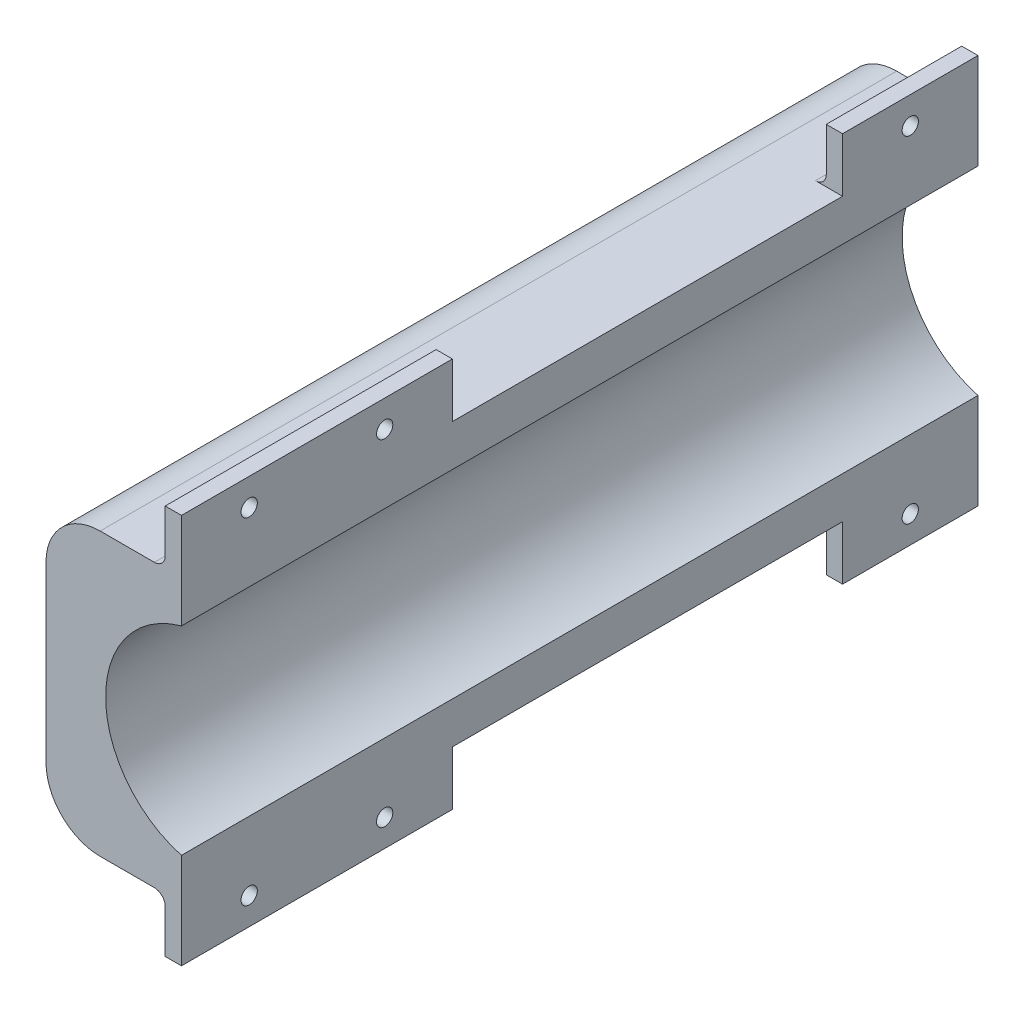
SolidWorks part; units mm, degrees
ref_plane "Front Plane" through (0, 0, 0) normal (0, 0, 1) x (1, 0, 0)
ref_plane "Top Plane" through (0, 0, 0) normal (0, 1, 0) x (1, 0, 0)
ref_plane "Right Plane" through (0, 0, 0) normal (1, 0, 0) x (0, 0, -1)
sketch "Sketch1" plane through (0, 0, 0) normal (0, 0, 1) x (1, 0, 0)
  line L0 (-91.4595, 15.9587) -> (-116.4595, 15.9587)
  line L1 (-91.4595, -36.0413) -> (-116.4595, -36.0413)
  line L2 (-116.4595, -36.0413) -> (-116.4595, 15.9587)
  line L3 (-91.4595, -28.3716) -> (-91.4595, -36.0413)
  line L4 (-91.4595, 15.9587) -> (-91.4595, 8.289)
  arc A0 (-91.4595, 8.289) -> (-91.4595, -28.3716) centre (-86.4595, -10.0413) ccw construction
  arc A1 (-91.4595, 8.289) -> (-91.4595, -28.3716) centre (-86.4595, -10.0413) ccw
extrude "Boss-Extrude1" add sketch "Sketch1" against normal blind 147
sketch "Sketch2" plane through (-91.4595, 0, 0) normal (1, 0, 0) x (0, 0, -1)
  line L0 (0, 15.9587) -> (50, 15.9587)
  line L1 (147, 15.9587) -> (0, 15.9587) construction
  line L2 (50, 5.9587) -> (50, 15.9587) construction
  line L3 (147, 15.9587) -> (122, 15.9587)
  line L4 (122, 15.9587) -> (122, 10.9587) construction
  line L5 (0, -10.0413) -> (147, -10.0413) construction
  line L6 (0, 8.289) -> (0, -28.3716) construction
  line L7 (147, -28.3716) -> (147, 8.289) construction
  line L8 (0, 15.9587) -> (12.5, 15.9587) construction
  line L9 (12.5, 15.9587) -> (12.5, 20.9587) construction
  line L10 (25, 15.9587) -> (25, 33.8054) construction
  line L11 (0, 15.9587) -> (0, 25.9587)
  line L12 (0, 25.9587) -> (50, 25.9587)
  line L13 (50, 25.9587) -> (50, 15.9587)
  line L14 (25, -36.0413) -> (25, -53.888) construction
  line L15 (12.5, -36.0413) -> (12.5, -41.0413) construction
  line L16 (0, -36.0413) -> (12.5, -36.0413) construction
  line L17 (50, -46.0413) -> (50, -36.0413)
  line L18 (0, -46.0413) -> (50, -46.0413)
  line L19 (0, -36.0413) -> (0, -46.0413)
  line L20 (0, -36.0413) -> (50, -36.0413)
  line L21 (134.5, 15.9587) -> (134.5, 20.9587) construction
  line L22 (122, 15.9587) -> (122, 25.9587)
  line L23 (122, 25.9587) -> (147, 25.9587)
  line L24 (147, 25.9587) -> (147, 15.9587)
  line L25 (134.5, -36.0413) -> (134.5, -41.0413) construction
  line L26 (147, -46.0413) -> (147, -36.0413)
  line L27 (122, -46.0413) -> (147, -46.0413)
  line L28 (122, -36.0413) -> (122, -46.0413)
  line L29 (147, -36.0413) -> (122, -36.0413)
  circle A0 centre (12.5, 20.9587) radius 1.5
  circle A1 centre (37.5, 20.9587) radius 1.5
  circle A2 centre (37.5, -41.0413) radius 1.5
  circle A3 centre (12.5, -41.0413) radius 1.5
  circle A4 centre (134.5, 20.9587) radius 1.5
  circle A5 centre (134.5, -41.0413) radius 1.5
extrude "Boss-Extrude2" add sketch "Sketch2" against normal blind 3
fillet "Fillet1" radius 10 2 edges at (-116.4595, 15.9587, -73.5) (-116.4595, -36.0413, -73.5)
fillet "Fillet2" radius 2 4 edges at (-94.4595, -36.0413, -25) (-94.4595, -36.0413, -134.5) (-94.4595, 15.9587, -134.5) (-94.4595, 15.9587, -25)
sketch "Sketch3" plane through (0, 0, 0) normal (0, 0, 1) x (1, 0, 0)
  line L5 (-91.4595, 15.9587) -> (-116.4595, 15.9587)
  line L6 (-116.4595, 15.9587) -> (-116.4595, -36.0413)
  line L7 (-116.4595, -36.0413) -> (-91.4595, -36.0413)
  line L8 (-91.4595, -36.0413) -> (-91.4595, -28.3716)
  line L9 (-91.4595, 8.289) -> (-91.4595, 15.9587)
  line L10 (-91.4595, 15.9587) -> (-116.4595, 15.9587)
  line L11 (-116.4595, 15.9587) -> (-116.4595, -36.0413)
  line L12 (-116.4595, -36.0413) -> (-91.4595, -36.0413)
  line L13 (-91.4595, -36.0413) -> (-91.4595, -28.3716)
  line L14 (-91.4595, 8.289) -> (-91.4595, 15.9587)
  arc A1 (-91.4595, 8.289) -> (-91.4595, -28.3716) centre (-86.4595, -10.0413) ccw
  arc A2 (-91.4595, 8.289) -> (-91.4595, -28.3716) centre (-86.4595, -10.0413) ccw
  dimension "D1" = 0
sketch "Sketch4" plane through (-91.4595, 0, 0) normal (1, 0, 0) x (0, 0, -1)
  line L4 (50, 25.9587) -> (0, 25.9587)
  line L5 (50, 15.9587) -> (50, 25.9587)
  line L6 (0, 15.9587) -> (50, 15.9587)
  line L7 (0, 25.9587) -> (0, 15.9587)
  line L8 (50, 25.9587) -> (0, 25.9587)
  line L9 (50, 15.9587) -> (50, 25.9587)
  line L10 (0, 15.9587) -> (50, 15.9587)
  line L11 (0, 25.9587) -> (0, 15.9587)
  line L12 (147, 25.9587) -> (122, 25.9587)
  line L13 (147, 15.9587) -> (147, 25.9587)
  line L14 (122, 15.9587) -> (147, 15.9587)
  line L15 (122, 25.9587) -> (122, 15.9587)
  line L16 (147, 25.9587) -> (122, 25.9587)
  line L17 (147, 15.9587) -> (147, 25.9587)
  line L18 (122, 15.9587) -> (147, 15.9587)
  line L19 (122, 25.9587) -> (122, 15.9587)
  line L20 (50, -46.0413) -> (50, -36.0413)
  line L21 (50, -36.0413) -> (0, -36.0413)
  line L22 (0, -36.0413) -> (0, -46.0413)
  line L23 (0, -46.0413) -> (50, -46.0413)
  line L24 (50, -46.0413) -> (50, -36.0413)
  line L25 (50, -36.0413) -> (0, -36.0413)
  line L26 (0, -36.0413) -> (0, -46.0413)
  line L27 (0, -46.0413) -> (50, -46.0413)
  line L28 (147, -46.0413) -> (147, -36.0413)
  line L29 (122, -46.0413) -> (147, -46.0413)
  line L30 (122, -36.0413) -> (122, -46.0413)
  line L31 (147, -36.0413) -> (122, -36.0413)
  line L32 (147, -46.0413) -> (147, -36.0413)
  line L33 (122, -46.0413) -> (147, -46.0413)
  line L34 (122, -36.0413) -> (122, -46.0413)
  line L35 (147, -36.0413) -> (122, -36.0413)
  circle A1 centre (37.5, 20.9587) radius 1.5
  circle A2 centre (37.5, 20.9587) radius 1.5
  circle A3 centre (12.5, 20.9587) radius 1.5
  circle A4 centre (12.5, 20.9587) radius 1.5
  circle A5 centre (134.5, -41.0413) radius 1.5
  circle A6 centre (134.5, -41.0413) radius 1.5
  circle A7 centre (134.5, 20.9587) radius 1.5
  circle A8 centre (134.5, 20.9587) radius 1.5
  circle A9 centre (12.5, -41.0413) radius 1.5
  circle A10 centre (12.5, -41.0413) radius 1.5
  circle A11 centre (37.5, -41.0413) radius 1.5
  circle A12 centre (37.5, -41.0413) radius 1.5
  dimension "D1" = 0
  dimension "D2" = 0
  dimension "D3" = 0
  dimension "D4" = 0
  dimension "D5" = 0
  dimension "D6" = 0
  dimension "D7" = 0
  dimension "D8" = 0
  dimension "D9" = 0
  dimension "D10" = 0
